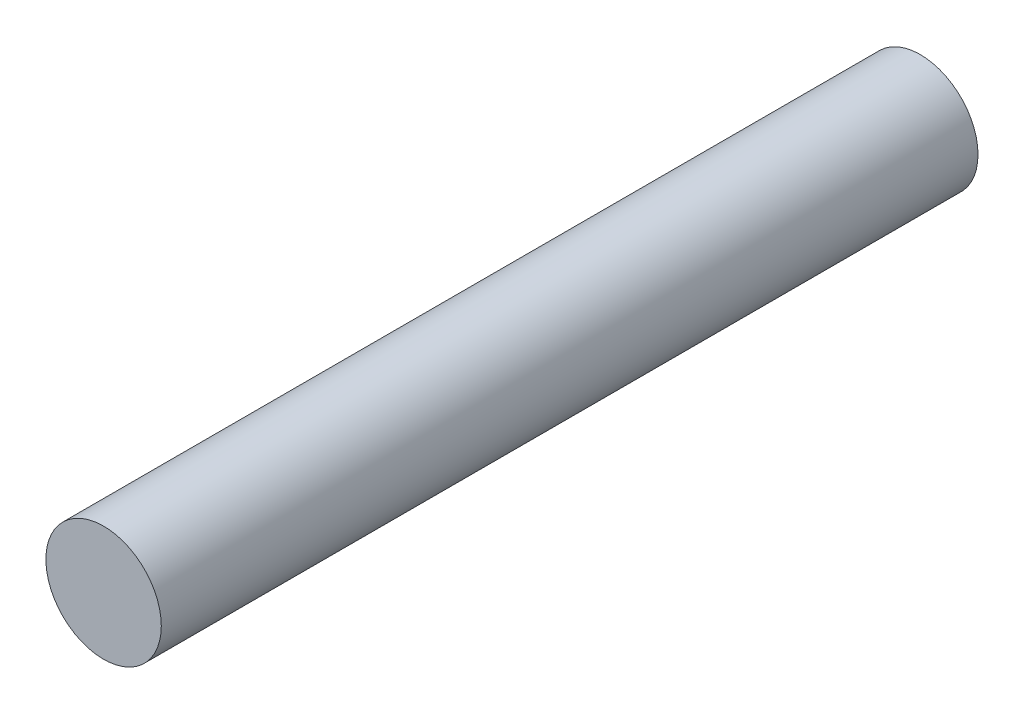
SolidWorks part; units mm, degrees
ref_plane "Front Plane" through (0, 0, 0) normal (0, 0, 1) x (1, 0, 0)
ref_plane "Top Plane" through (0, 0, 0) normal (0, 1, 0) x (1, 0, 0)
ref_plane "Right Plane" through (0, 0, 0) normal (1, 0, 0) x (0, 0, -1)
sketch "Sketch1" plane through (0, 0, 0) normal (0, 0, 1) x (1, 0, 0)
  line L0 (0, 0) -> (0, 149.075) construction
  line L1 (0, 0) -> (176.0047, 0) construction
  circle A0 centre (0, 0) radius 29.815
  dimension "D1" = 59.63
extrude "Boss-Extrude1" add sketch "Sketch1" along normal blind 292 and the other way blind 130
